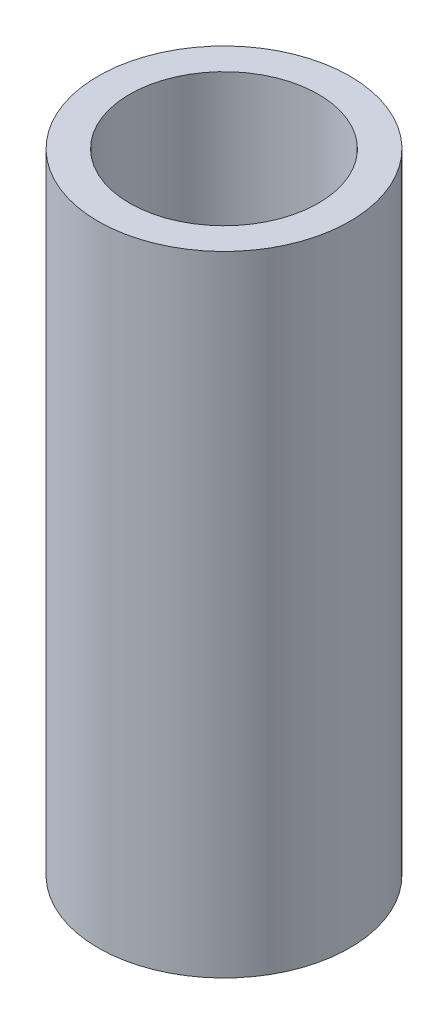
SolidWorks part; units mm, degrees
ref_plane "Front Plane" through (0, 0, 0) normal (0, 0, 1) x (1, 0, 0)
ref_plane "Top Plane" through (0, 0, 0) normal (0, 1, 0) x (1, 0, 0)
ref_plane "Right Plane" through (0, 0, 0) normal (1, 0, 0) x (0, 0, -1)
sketch "Sketch1" plane through (0, 0, 0) normal (0, 1, 0) x (1, 0, 0)
  circle A0 centre (0, 0) radius 20
  circle A1 centre (0, 0) radius 15
extrude "BaseCylinder" add sketch "Sketch1" along normal blind 100
